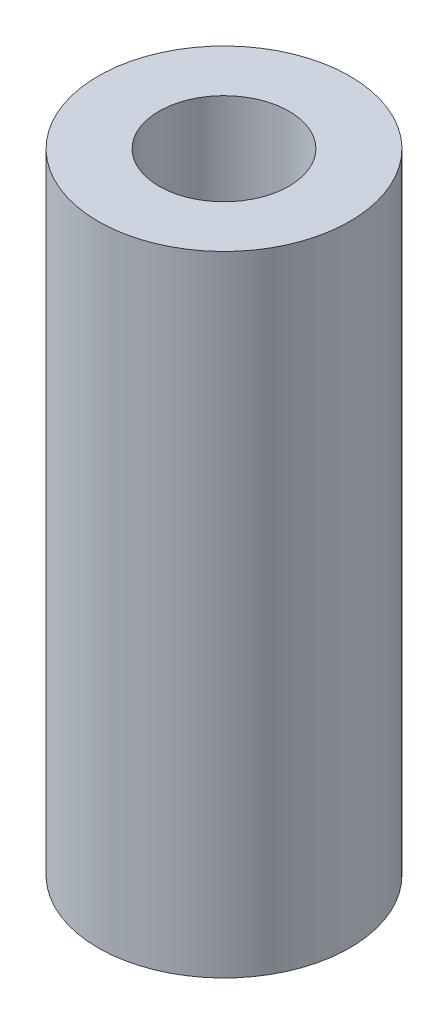
SolidWorks part; units mm, degrees
ref_plane "前视基准面" through (0, 0, 0) normal (0, 0, 1) x (1, 0, 0)
ref_plane "上视基准面" through (0, 0, 0) normal (0, 1, 0) x (1, 0, 0)
ref_plane "右视基准面" through (0, 0, 0) normal (1, 0, 0) x (0, 0, -1)
other "Configuration Table"
sketch "草图1" plane through (0, 0, 0) normal (0, 1, 0) x (1, 0, 0)
  circle A0 centre (0, 0) radius 3
  circle A1 centre (0, 0) radius 1.55
  dimension "D1" = 6
  dimension "D2" = 3.1
extrude "凸台-拉伸1" add sketch "草图1" along normal blind 15
